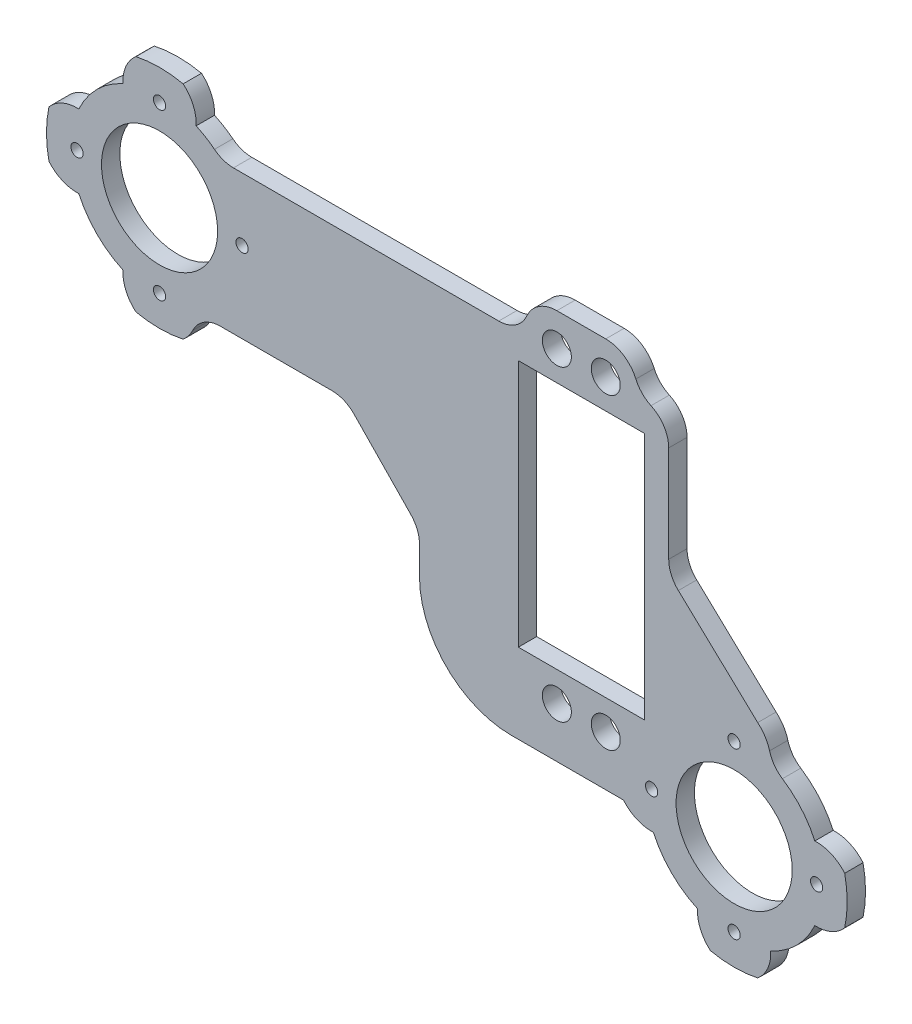
SolidWorks part; units mm, degrees
ref_plane "Front Plane" through (0, 0, 0) normal (0, 0, 1) x (1, 0, 0)
ref_plane "Top Plane" through (0, 0, 0) normal (0, 1, 0) x (1, 0, 0)
ref_plane "Right Plane" through (0, 0, 0) normal (1, 0, 0) x (0, 0, -1)
sketch "Sketch1" plane through (0, 0, 0) normal (0, 0, 1) x (1, 0, 0)
  line L0 (0, 0) -> (-25, 0) construction
  line L1 (-25, 0) -> (-25, 19.5) construction
  line L2 (0, 0) -> (-94, 0) construction
  line L3 (-94, 0) -> (-94, 43.5) construction
  dimension "D1" = 25
  dimension "D2" = 19.5
  dimension "D3" = 43.5
  dimension "D4" = 94
sketch "Sketch13" plane through (0, 0, 0) normal (0, 0, 1) x (1, 0, 0)
  line L0 (0, -18.5) -> (0, 18.5) construction
  line L2 (0, 0) -> (0, 13.5) construction
  circle A0 centre (0, 0) radius 2.25 construction
  circle A1 centre (0, 0) radius 9.5
  circle A2 centre (0, 0) radius 11.5 construction
  circle A3 centre (0, 0) radius 16.5 construction
  circle A4 centre (0, 0) radius 18.5
  circle A5 centre (0, 13.5) radius 1
  circle A6 centre (0, 0) radius 14.5
  circle A8 centre (0, 13.5) radius 3 construction
  circle A9 centre (0, 13.5) radius 6
  circle A10 centre (13.5, 0) radius 6
  circle A11 centre (13.5, 0) radius 3 construction
  circle A12 centre (13.5, 0) radius 1
  circle A13 centre (0, -13.5) radius 6
  circle A14 centre (0, -13.5) radius 3 construction
  circle A15 centre (0, -13.5) radius 1
  circle A16 centre (-13.5, 0) radius 6
  circle A17 centre (-13.5, 0) radius 3 construction
  circle A18 centre (-13.5, 0) radius 1
  dimension "D1" = 4.5
  dimension "D2" = 19
  dimension "D3" = 23
  dimension "D4" = 33
  dimension "D5" = 2
  dimension "D7" = 2
  dimension "D6" = 29
  dimension "D8" = 13.5
  dimension "D9" = 2
  dimension "D10" = 3
  dimension "D11" = 4
extrude "Boss-Extrude1" add sketch "Sketch13" along normal blind 3 contours A16 A1 A9 A6 | A13 A6 A10 A1 | A6 A16 A4 | A6 A18 A16 A1 | A16 A6 A13 A1 | A6 A15 A13 A1 | A6 A13 A4 | A6 A12 A10 A1 | A4 A10 A6 | A10 A6 A9 A1 | A6 A9 A1 A5 | A4 A9 A6
move or copy body "Body-Move/Copy1" bodies to move or copy 124 copy yes number of copies 1 translate (-94, 43.5, 0)
sketch "Sketch14" plane through (0, 0, 0) normal (0, 0, -1) x (-1, 0, 0)
  line L0 (94, 0) -> (94, 43.5) construction
  line L1 (0, 0) -> (94, 0) construction
  line L2 (25, 0) -> (25, 19.5) construction
  line L3 (94, 0) -> (94, 43.5) construction
  line L4 (0, 0) -> (94, 0) construction
  line L5 (25, 0) -> (25, 19.5) construction
  line L6 (35, 9.5) -> (15, 9.5) construction
  line L7 (35, 49.5) -> (15, 49.5) construction
  line L8 (15, 9.5) -> (15, 49.5) construction
  line L9 (35, 9.5) -> (35, 49.5) construction
  line L10 (35, 19.5) -> (15, 19.5) construction
  line L11 (35.3, 49.8) -> (14.7, 49.8)
  line L12 (14.7, 9.2) -> (14.7, 49.8)
  line L13 (35.3, 9.2) -> (14.7, 9.2)
  line L14 (35.3, 9.2) -> (35.3, 49.8)
  line L15 (35, 54.65) -> (15, 54.65) construction
  line L16 (25, 54.65) -> (25, 49.5) construction
  line L17 (35, 29.5) -> (15, 29.5) construction
  line L18 (39.3, 5.2) -> (39.3, 53.8)
  line L19 (39.3, 53.8) -> (10.7, 53.8)
  line L20 (10.7, 5.2) -> (10.7, 53.8)
  line L21 (39.3, 5.2) -> (10.7, 5.2)
  circle A0 centre (21, 54.65) radius 2.375
  circle A1 centre (29, 54.65) radius 2.375
  circle A2 centre (21, 4.35) radius 2.375
  circle A3 centre (29, 4.35) radius 2.375
  circle A4 centre (29, 4.35) radius 5.375
  circle A5 centre (21, 4.35) radius 5.375
  circle A6 centre (29, 54.65) radius 5.375
  circle A7 centre (21, 54.65) radius 5.375
  point P12 (25, 19.5)
  arc M7 (13.2037, 5.9927) -> (5.9927, 13.2037) centre (0, 0) ccw
  arc M21 (18.0926, -3.8611) -> (18.0926, 3.8611) centre (0, 0) ccw
  arc M22 (18.0926, 3.8611) -> (13.2037, 5.9927) centre (13.5, 0) ccw
  dimension "D7" = 4.75
  dimension "D1" = 40
  dimension "D2" = 20
  dimension "D3" = 10
  dimension "D6" = 4
  dimension "D4" = 0.3
  dimension "D5" = 5.15
  dimension "D8" = 3
  dimension "D9" = 4
extrude "Boss-Extrude2" add sketch "Sketch14" against normal blind 3 contours L19 A6 L11 L14 L13 A4 L21 L18 | A7 L19 L20 A5 L13 L12 L11 M7 M22 | L19 A7 L11 A6 A0 | A7 A6 L11 L19 A1 | A4 A5 L21 A3 L13 | A5 L21 A2 A4 L13 M22 | L13 A5 A4 | A5 A4 L21 | A5 L21 A4 | L21 A5 A4 A3 | A5 A4 L21 A2 M22 M21 | A6 A7 L19 | L19 A7 A6 | A7 L19 A1 A6 | A6 A7 L19 A0 | A7 L11 A6
sketch "Sketch15" plane through (0, 0, 0) normal (0, 0, -1) x (-1, 0, 0)
  line L0 (34.3074, 5.2) -> (39.3, 5.2) construction
  line L1 (39.3, 5.2) -> (39.3, 53.8) construction
  line L2 (39.3, 53.8) -> (34.3074, 53.8) construction
  line L3 (15.6926, 53.8) -> (10.7, 53.8) construction
  line L4 (10.7, 53.8) -> (10.7, 9.7857) construction
  line L5 (34.3074, 5.2) -> (39.3, 5.2)
  line L6 (39.3, 5.2) -> (39.3, 53.8)
  line L7 (39.3, 53.8) -> (34.3074, 53.8)
  line L8 (15.6926, 53.8) -> (10.7, 53.8)
  line L9 (10.7, 53.8) -> (10.7, 9.7857)
  line L10 (39.3, 53.8) -> (83.7941, 53.8)
  line L11 (88.0073, 30.2963) -> (39.3, 30.2963)
  line L12 (10.7, 31.7929) -> (-3.8611, 18.0926)
  line L13 (29, -1.025) -> (51.4768, -1.025)
  line L14 (51.4768, -1.025) -> (51.4768, 17.7481)
  line L15 (39.3, 5.2) -> (63.6537, 30.2963)
  line L16 (18.0926, -3.8611) -> (51.4768, -3.8611)
  line L17 (51.4768, -3.8611) -> (51.4768, -1.025)
  line L18 (21, 60.025) -> (29, 60.025)
  arc A0 (18.0926, -3.8611) -> (18.4955, -0.4059) centre (0, 0) ccw construction
  arc A1 (18.4955, -0.4059) -> (25, 0.7596) centre (21, 4.35) ccw construction
  arc A2 (25, 0.7596) -> (34.3074, 5.2) centre (29, 4.35) ccw construction
  arc A3 (34.3074, 53.8) -> (25, 58.2404) centre (29, 54.65) ccw construction
  arc A4 (25, 58.2404) -> (15.6926, 53.8) centre (21, 54.65) ccw construction
  arc A5 (10.7, 9.7857) -> (5.9927, 13.2037) centre (0, 0) ccw construction
  arc A6 (5.9927, 13.2037) -> (3.8611, 18.0926) centre (0, 13.5) ccw construction
  arc A7 (3.8611, 18.0926) -> (-3.8611, 18.0926) centre (0, 0) ccw construction
  arc A8 (-3.8611, 18.0926) -> (-5.9927, 13.2037) centre (0, 13.5) ccw construction
  arc A9 (-5.9927, 13.2037) -> (-13.2037, 5.9927) centre (0, 0) ccw construction
  arc A10 (-13.2037, 5.9927) -> (-18.0926, 3.8611) centre (-13.5, 0) ccw construction
  arc A11 (-18.0926, 3.8611) -> (-18.0926, -3.8611) centre (0, 0) ccw construction
  arc A12 (-18.0926, -3.8611) -> (-13.2037, -5.9927) centre (-13.5, 0) ccw construction
  arc A13 (-13.2037, -5.9927) -> (-5.9927, -13.2037) centre (0, 0) ccw construction
  arc A14 (-5.9927, -13.2037) -> (-3.8611, -18.0926) centre (0, -13.5) ccw construction
  arc A15 (-3.8611, -18.0926) -> (3.8611, -18.0926) centre (0, 0) ccw construction
  arc A16 (3.8611, -18.0926) -> (5.9927, -13.2037) centre (0, -13.5) ccw construction
  arc A17 (5.9927, -13.2037) -> (13.2037, -5.9927) centre (0, 0) ccw construction
  arc A18 (13.2037, -5.9927) -> (18.0926, -3.8611) centre (13.5, 0) ccw construction
  arc A19 (107.2037, 49.4927) -> (99.9927, 56.7037) centre (94, 43.5) ccw construction
  arc A20 (99.9927, 56.7037) -> (97.8611, 61.5926) centre (94, 57) ccw construction
  arc A21 (97.8611, 61.5926) -> (90.1389, 61.5926) centre (94, 43.5) ccw construction
  arc A22 (90.1389, 61.5926) -> (88.0073, 56.7037) centre (94, 57) ccw construction
  arc A23 (88.0073, 56.7037) -> (80.7963, 49.4927) centre (94, 43.5) ccw construction
  arc A24 (80.7963, 49.4927) -> (75.9074, 47.3611) centre (80.5, 43.5) ccw construction
  arc A25 (75.9074, 47.3611) -> (75.9074, 39.6389) centre (94, 43.5) ccw construction
  arc A26 (75.9074, 39.6389) -> (80.7963, 37.5073) centre (80.5, 43.5) ccw construction
  arc A27 (80.7963, 37.5073) -> (88.0073, 30.2963) centre (94, 43.5) ccw construction
  arc A28 (88.0073, 30.2963) -> (90.1389, 25.4074) centre (94, 30) ccw construction
  arc A29 (90.1389, 25.4074) -> (97.8611, 25.4074) centre (94, 43.5) ccw construction
  arc A30 (97.8611, 25.4074) -> (99.9927, 30.2963) centre (94, 30) ccw construction
  arc A31 (99.9927, 30.2963) -> (107.2037, 37.5073) centre (94, 43.5) ccw construction
  arc A32 (107.2037, 37.5073) -> (112.0926, 39.6389) centre (107.5, 43.5) ccw construction
  arc A33 (112.0926, 39.6389) -> (112.0926, 47.3611) centre (94, 43.5) ccw construction
  arc A34 (112.0926, 47.3611) -> (107.2037, 49.4927) centre (107.5, 43.5) ccw construction
  arc A35 (18.0926, -3.8611) -> (18.4955, -0.4059) centre (0, 0) ccw
  arc A36 (18.4955, -0.4059) -> (25, 0.7596) centre (21, 4.35) ccw
  arc A37 (25, 0.7596) -> (34.3074, 5.2) centre (29, 4.35) ccw
  arc A38 (34.3074, 53.8) -> (25, 58.2404) centre (29, 54.65) ccw
  arc A39 (25, 58.2404) -> (15.6926, 53.8) centre (21, 54.65) ccw
  arc A40 (10.7, 9.7857) -> (5.9927, 13.2037) centre (0, 0) ccw
  arc A41 (5.9927, 13.2037) -> (3.8611, 18.0926) centre (0, 13.5) ccw
  arc A42 (3.8611, 18.0926) -> (-3.8611, 18.0926) centre (0, 0) ccw
  arc A43 (-3.8611, 18.0926) -> (-5.9927, 13.2037) centre (0, 13.5) ccw
  arc A44 (-5.9927, 13.2037) -> (-13.2037, 5.9927) centre (0, 0) ccw
  arc A45 (-13.2037, 5.9927) -> (-18.0926, 3.8611) centre (-13.5, 0) ccw
  arc A46 (-18.0926, 3.8611) -> (-18.0926, -3.8611) centre (0, 0) ccw
  arc A47 (-18.0926, -3.8611) -> (-13.2037, -5.9927) centre (-13.5, 0) ccw
  arc A48 (-13.2037, -5.9927) -> (-5.9927, -13.2037) centre (0, 0) ccw
  arc A49 (-5.9927, -13.2037) -> (-3.8611, -18.0926) centre (0, -13.5) ccw
  arc A50 (-3.8611, -18.0926) -> (3.8611, -18.0926) centre (0, 0) ccw
  arc A51 (3.8611, -18.0926) -> (5.9927, -13.2037) centre (0, -13.5) ccw
  arc A52 (5.9927, -13.2037) -> (13.2037, -5.9927) centre (0, 0) ccw
  arc A53 (13.2037, -5.9927) -> (18.0926, -3.8611) centre (13.5, 0) ccw
  arc A54 (107.2037, 49.4927) -> (99.9927, 56.7037) centre (94, 43.5) ccw
  arc A55 (99.9927, 56.7037) -> (97.8611, 61.5926) centre (94, 57) ccw
  arc A56 (97.8611, 61.5926) -> (90.1389, 61.5926) centre (94, 43.5) ccw
  arc A57 (90.1389, 61.5926) -> (88.0073, 56.7037) centre (94, 57) ccw
  arc A58 (88.0073, 56.7037) -> (80.7963, 49.4927) centre (94, 43.5) ccw
  arc A59 (80.7963, 49.4927) -> (75.9074, 47.3611) centre (80.5, 43.5) ccw
  arc A60 (75.9074, 47.3611) -> (75.9074, 39.6389) centre (94, 43.5) ccw
  arc A61 (75.9074, 39.6389) -> (80.7963, 37.5073) centre (80.5, 43.5) ccw
  arc A62 (80.7963, 37.5073) -> (88.0073, 30.2963) centre (94, 43.5) ccw
  arc A63 (88.0073, 30.2963) -> (90.1389, 25.4074) centre (94, 30) ccw
  arc A64 (90.1389, 25.4074) -> (97.8611, 25.4074) centre (94, 43.5) ccw
  arc A65 (97.8611, 25.4074) -> (99.9927, 30.2963) centre (94, 30) ccw
  arc A66 (99.9927, 30.2963) -> (107.2037, 37.5073) centre (94, 43.5) ccw
  arc A67 (107.2037, 37.5073) -> (112.0926, 39.6389) centre (107.5, 43.5) ccw
  arc A68 (112.0926, 39.6389) -> (112.0926, 47.3611) centre (94, 43.5) ccw
  arc A69 (112.0926, 47.3611) -> (107.2037, 49.4927) centre (107.5, 43.5) ccw
  point P23 (51.4768, 17.7481)
  arc M49 (88.0073, 56.7037) -> (80.7963, 49.4927) centre (94, 43.5) ccw
  arc M50 (80.7963, 49.4927) -> (75.9074, 47.3611) centre (80.5, 43.5) ccw
  arc M51 (75.9074, 47.3611) -> (75.9074, 39.6389) centre (94, 43.5) ccw
  arc M52 (75.9074, 39.6389) -> (80.7963, 37.5073) centre (80.5, 43.5) ccw
  arc M53 (80.7963, 37.5073) -> (88.0073, 30.2963) centre (94, 43.5) ccw
extrude "Boss-Extrude4" add sketch "Sketch15" against normal blind 3 contours A37 L13 L14 L15 L5 | L6 L15 L11 | L11 L10 L6 M53 M52 M51 M50 M49 | A42 A41 A40 L9 L12 | A39 A38 L18 | A37 A36 A35 L16 L17 L13
fillet "Fillet1" radius 5 8 edges at (5.9927, 13.2037, 1.5) (-15.6926, 53.8, 1.5) (-34.3074, 53.8, 1.5) (-10.7, 31.7929, 1.5) (-88.0073, 30.2963, 1.5) (-83.7941, 53.8, 1.5) (-63.6537, 30.2963, 1.5) (-51.4768, 17.7481, 1.5)
fillet "Fillet2" radius 5 1 edges at (-10.7, 53.8, 1.5)
fillet "Fillet3" radius 15 1 edges at (-51.4768, -3.8611, 1.5)
